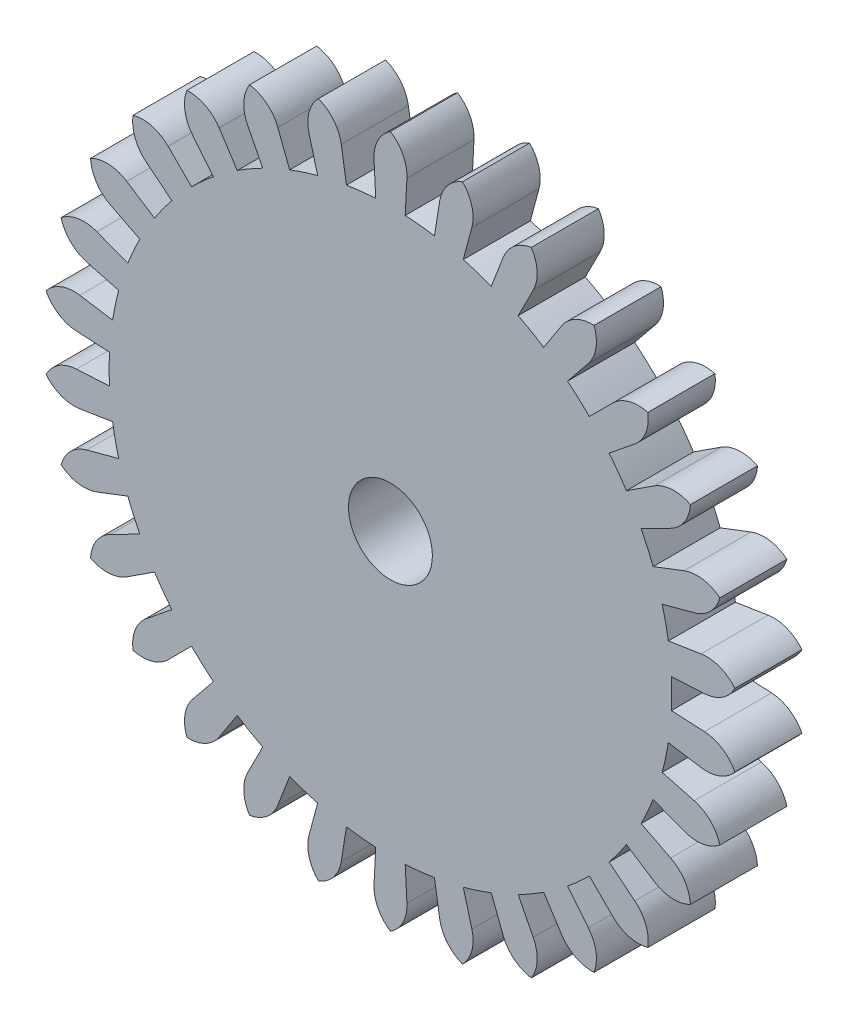
SolidWorks part; units mm, degrees
material "AISI 347 Annealed Stainless Steel (SS)"
ref_plane "Front Plane" through (0, 0, 0) normal (0, 0, 1) x (1, 0, 0)
ref_plane "Top Plane" through (0, 0, 0) normal (0, 1, 0) x (1, 0, 0)
ref_plane "Right Plane" through (0, 0, 0) normal (1, 0, 0) x (0, 0, -1)
sketch "Sketch1" plane through (0, 0, 0) normal (0, 0, 1) x (1, 0, 0)
  line L0 (0, 0) -> (0, 5.0077) construction
  line L1 (-0.1756, 3.3504) -> (-0.1963, 3.7449)
  line L2 (0.1756, 3.3504) -> (0.1963, 3.7449)
  line L3 (0.5248, 3.3137) -> (0.5866, 3.7038)
  line L4 (0.8684, 3.2407) -> (0.9706, 3.6222)
  line L5 (1.2023, 3.1322) -> (1.3439, 3.5009)
  line L6 (1.5232, 2.9893) -> (1.7025, 3.3413)
  line L7 (1.8272, 2.8138) -> (2.0424, 3.145)
  line L8 (2.1114, 2.6073) -> (2.36, 2.9143)
  line L9 (2.3723, 2.3724) -> (2.6516, 2.6517)
  line L10 (2.6073, 2.1114) -> (2.9143, 2.3599)
  line L11 (2.8137, 1.8273) -> (3.145, 2.0424)
  line L12 (2.9893, 1.5231) -> (3.3413, 1.7024)
  line L13 (3.1322, 1.2023) -> (3.5009, 1.3439)
  line L14 (3.2407, 0.8683) -> (3.6222, 0.9705)
  line L15 (3.3137, 0.5249) -> (3.7038, 0.5867)
  line L16 (3.3504, 0.1756) -> (3.7449, 0.1962)
  line L17 (3.3504, -0.1756) -> (3.7449, -0.1962)
  line L18 (3.3137, -0.5249) -> (3.7038, -0.5867)
  line L19 (3.2407, -0.8683) -> (3.6222, -0.9705)
  line L20 (3.1322, -1.2023) -> (3.5009, -1.3439)
  line L21 (2.9893, -1.5231) -> (3.3413, -1.7024)
  line L22 (2.8137, -1.8273) -> (3.145, -2.0424)
  line L23 (2.6073, -2.1114) -> (2.9143, -2.3599)
  line L24 (2.3723, -2.3724) -> (2.6516, -2.6517)
  line L25 (2.1114, -2.6073) -> (2.36, -2.9143)
  line L26 (1.8272, -2.8138) -> (2.0424, -3.145)
  line L27 (1.5232, -2.9893) -> (1.7025, -3.3413)
  line L28 (1.2023, -3.1322) -> (1.3439, -3.5009)
  line L29 (0.8684, -3.2407) -> (0.9706, -3.6222)
  line L30 (0.5248, -3.3137) -> (0.5866, -3.7038)
  line L31 (0.1756, -3.3504) -> (0.1963, -3.7449)
  line L32 (-0.1756, -3.3504) -> (-0.1963, -3.7449)
  line L33 (-0.5248, -3.3137) -> (-0.5866, -3.7038)
  line L34 (-0.8684, -3.2407) -> (-0.9706, -3.6222)
  line L35 (-1.2023, -3.1322) -> (-1.3439, -3.5009)
  line L36 (-1.5232, -2.9893) -> (-1.7025, -3.3413)
  line L37 (-1.8272, -2.8138) -> (-2.0424, -3.145)
  line L38 (-2.1114, -2.6073) -> (-2.36, -2.9143)
  line L39 (-2.3723, -2.3724) -> (-2.6516, -2.6517)
  line L40 (-2.6073, -2.1114) -> (-2.9143, -2.3599)
  line L41 (-2.8137, -1.8273) -> (-3.145, -2.0424)
  line L42 (-2.9893, -1.5231) -> (-3.3413, -1.7024)
  line L43 (-3.1322, -1.2023) -> (-3.5009, -1.3439)
  line L44 (-3.2407, -0.8683) -> (-3.6222, -0.9705)
  line L45 (-3.3137, -0.5249) -> (-3.7038, -0.5867)
  line L46 (-3.3504, -0.1756) -> (-3.7449, -0.1962)
  line L47 (-3.3504, 0.1756) -> (-3.7449, 0.1962)
  line L48 (-3.3137, 0.5249) -> (-3.7038, 0.5867)
  line L49 (-3.2407, 0.8683) -> (-3.6222, 0.9705)
  line L50 (-3.1322, 1.2023) -> (-3.5009, 1.3439)
  line L51 (-2.9893, 1.5231) -> (-3.3413, 1.7024)
  line L52 (-2.8137, 1.8273) -> (-3.145, 2.0424)
  line L53 (-2.6073, 2.1114) -> (-2.9143, 2.3599)
  line L54 (-2.3723, 2.3724) -> (-2.6516, 2.6517)
  line L55 (-2.1114, 2.6073) -> (-2.36, 2.9143)
  line L56 (-1.8272, 2.8138) -> (-2.0424, 3.145)
  line L57 (-1.5232, 2.9893) -> (-1.7025, 3.3413)
  line L58 (-1.2023, 3.1322) -> (-1.3439, 3.5009)
  line L59 (-0.8684, 3.2407) -> (-0.9706, 3.6222)
  line L60 (-0.5248, 3.3137) -> (-0.5866, 3.7038)
  arc A0 (0.5248, 3.3137) -> (0.1756, 3.3504) centre (0, 0) ccw
  arc A1 (1.2023, 3.1322) -> (0.8684, 3.2407) centre (0, 0) ccw
  arc A2 (-0.1756, 3.3504) -> (-0.5248, 3.3137) centre (0, 0) ccw
  arc A3 (0.1963, 3.7449) -> (0, 4.13) centre (-0.2353, 3.7675) ccw
  arc A4 (-0.1963, 3.7449) -> (0, 4.13) centre (0.2353, 3.7675) cw
  arc A5 (0.9706, 3.6222) -> (0.8587, 4.0397) centre (0.5531, 3.7341) ccw
  arc A6 (0.5866, 3.7038) -> (0.8587, 4.0397) centre (1.0135, 3.6362) cw
  arc A7 (1.7025, 3.3413) -> (1.6798, 3.7729) centre (1.3174, 3.5375) ccw
  arc A8 (1.3439, 3.5009) -> (1.6798, 3.7729) centre (1.7474, 3.3461) cw
  arc A9 (2.36, 2.9143) -> (2.4276, 3.3412) centre (2.0241, 3.1863) ccw
  arc A10 (2.0424, 3.145) -> (2.4276, 3.3412) centre (2.4049, 2.9096) cw
  arc A11 (2.9143, 2.3599) -> (3.0692, 2.7635) centre (2.6423, 2.6958) ccw
  arc A12 (2.6516, 2.6517) -> (3.0692, 2.7635) centre (2.9572, 2.3461) cw
  arc A13 (3.3413, 1.7024) -> (3.5767, 2.065) centre (3.1451, 2.0875) ccw
  arc A14 (3.145, 2.0424) -> (3.5767, 2.065) centre (3.3804, 1.6799) cw
  arc A15 (3.6222, 0.9705) -> (3.9279, 1.2762) centre (3.5104, 1.388) ccw
  arc A16 (3.5009, 1.3439) -> (3.9279, 1.2762) centre (3.6558, 0.9404) cw
  arc A17 (3.7449, 0.1962) -> (4.1074, 0.4317) centre (3.7222, 0.6278) ccw
  arc A18 (3.7038, 0.5867) -> (4.1074, 0.4317) centre (3.7714, 0.1598) cw
  arc A19 (3.7038, -0.5867) -> (4.1074, -0.4317) centre (3.7714, -0.1598) ccw
  arc A20 (3.7449, -0.1962) -> (4.1074, -0.4317) centre (3.7222, -0.6278) cw
  arc A21 (3.5009, -1.3439) -> (3.9279, -1.2762) centre (3.6558, -0.9404) ccw
  arc A22 (3.6222, -0.9705) -> (3.9279, -1.2762) centre (3.5104, -1.388) cw
  arc A23 (3.145, -2.0424) -> (3.5767, -2.065) centre (3.3804, -1.6799) ccw
  arc A24 (3.3413, -1.7024) -> (3.5767, -2.065) centre (3.1451, -2.0875) cw
  arc A25 (2.6516, -2.6517) -> (3.0692, -2.7635) centre (2.9572, -2.3461) ccw
  arc A26 (2.9143, -2.3599) -> (3.0692, -2.7635) centre (2.6423, -2.6958) cw
  arc A27 (2.0424, -3.145) -> (2.4276, -3.3412) centre (2.4049, -2.9096) ccw
  arc A28 (2.36, -2.9143) -> (2.4276, -3.3412) centre (2.0241, -3.1863) cw
  arc A29 (1.3439, -3.5009) -> (1.6798, -3.7729) centre (1.7474, -3.3461) ccw
  arc A30 (1.7025, -3.3413) -> (1.6798, -3.7729) centre (1.3174, -3.5375) cw
  arc A31 (0.5866, -3.7038) -> (0.8587, -4.0397) centre (1.0135, -3.6362) ccw
  arc A32 (0.9706, -3.6222) -> (0.8587, -4.0397) centre (0.5531, -3.7341) cw
  arc A33 (-0.1963, -3.7449) -> (0, -4.13) centre (0.2353, -3.7675) ccw
  arc A34 (0.1963, -3.7449) -> (0, -4.13) centre (-0.2353, -3.7675) cw
  arc A35 (-0.9706, -3.6222) -> (-0.8587, -4.0397) centre (-0.5531, -3.7341) ccw
  arc A36 (-0.5866, -3.7038) -> (-0.8587, -4.0397) centre (-1.0135, -3.6362) cw
  arc A37 (-1.7025, -3.3413) -> (-1.6798, -3.7729) centre (-1.3174, -3.5375) ccw
  arc A38 (-1.3439, -3.5009) -> (-1.6798, -3.7729) centre (-1.7474, -3.3461) cw
  arc A39 (-2.36, -2.9143) -> (-2.4276, -3.3412) centre (-2.0241, -3.1863) ccw
  arc A40 (-2.0424, -3.145) -> (-2.4276, -3.3412) centre (-2.4049, -2.9096) cw
  arc A41 (-2.9143, -2.3599) -> (-3.0692, -2.7635) centre (-2.6423, -2.6958) ccw
  arc A42 (-2.6516, -2.6517) -> (-3.0692, -2.7635) centre (-2.9572, -2.3461) cw
  arc A43 (-3.3413, -1.7024) -> (-3.5767, -2.065) centre (-3.1451, -2.0875) ccw
  arc A44 (-3.145, -2.0424) -> (-3.5767, -2.065) centre (-3.3804, -1.6799) cw
  arc A45 (-3.6222, -0.9705) -> (-3.9279, -1.2762) centre (-3.5104, -1.388) ccw
  arc A46 (-3.5009, -1.3439) -> (-3.9279, -1.2762) centre (-3.6558, -0.9404) cw
  arc A47 (-3.7449, -0.1962) -> (-4.1074, -0.4317) centre (-3.7222, -0.6278) ccw
  arc A48 (-3.7038, -0.5867) -> (-4.1074, -0.4317) centre (-3.7714, -0.1598) cw
  arc A49 (-3.7038, 0.5867) -> (-4.1074, 0.4317) centre (-3.7714, 0.1598) ccw
  arc A50 (-3.7449, 0.1962) -> (-4.1074, 0.4317) centre (-3.7222, 0.6278) cw
  arc A51 (-3.5009, 1.3439) -> (-3.9279, 1.2762) centre (-3.6558, 0.9404) ccw
  arc A52 (-3.6222, 0.9705) -> (-3.9279, 1.2762) centre (-3.5104, 1.388) cw
  arc A53 (-3.145, 2.0424) -> (-3.5767, 2.065) centre (-3.3804, 1.6799) ccw
  arc A54 (-3.3413, 1.7024) -> (-3.5767, 2.065) centre (-3.1451, 2.0875) cw
  arc A55 (-2.6516, 2.6517) -> (-3.0692, 2.7635) centre (-2.9572, 2.3461) ccw
  arc A56 (-2.9143, 2.3599) -> (-3.0692, 2.7635) centre (-2.6423, 2.6958) cw
  arc A57 (-2.0424, 3.145) -> (-2.4276, 3.3412) centre (-2.4049, 2.9096) ccw
  arc A58 (-2.36, 2.9143) -> (-2.4276, 3.3412) centre (-2.0241, 3.1863) cw
  arc A59 (-1.3439, 3.5009) -> (-1.6798, 3.7729) centre (-1.7474, 3.3461) ccw
  arc A60 (-1.7025, 3.3413) -> (-1.6798, 3.7729) centre (-1.3174, 3.5375) cw
  arc A61 (-0.5866, 3.7038) -> (-0.8587, 4.0397) centre (-1.0135, 3.6362) ccw
  arc A62 (-0.9706, 3.6222) -> (-0.8587, 4.0397) centre (-0.5531, 3.7341) cw
  arc A63 (-0.8684, 3.2407) -> (-1.2023, 3.1322) centre (0, 0) ccw
  arc A64 (-1.5232, 2.9893) -> (-1.8272, 2.8138) centre (0, 0) ccw
  arc A65 (-2.1114, 2.6073) -> (-2.3723, 2.3724) centre (0, 0) ccw
  arc A66 (-2.6073, 2.1114) -> (-2.8137, 1.8273) centre (0, 0) ccw
  arc A67 (-2.9893, 1.5231) -> (-3.1322, 1.2023) centre (0, 0) ccw
  arc A68 (-3.2407, 0.8683) -> (-3.3137, 0.5249) centre (0, 0) ccw
  arc A69 (-3.3504, 0.1756) -> (-3.3504, -0.1756) centre (0, 0) ccw
  arc A70 (-3.3137, -0.5249) -> (-3.2407, -0.8683) centre (0, 0) ccw
  arc A71 (-3.1322, -1.2023) -> (-2.9893, -1.5231) centre (0, 0) ccw
  arc A72 (-2.8137, -1.8273) -> (-2.6073, -2.1114) centre (0, 0) ccw
  arc A73 (-2.3723, -2.3724) -> (-2.1114, -2.6073) centre (0, 0) ccw
  arc A74 (-1.8272, -2.8138) -> (-1.5232, -2.9893) centre (0, 0) ccw
  arc A75 (-1.2023, -3.1322) -> (-0.8684, -3.2407) centre (0, 0) ccw
  arc A76 (-0.5248, -3.3137) -> (-0.1756, -3.3504) centre (0, 0) ccw
  arc A77 (0.1756, -3.3504) -> (0.5248, -3.3137) centre (0, 0) ccw
  arc A78 (0.8684, -3.2407) -> (1.2023, -3.1322) centre (0, 0) ccw
  arc A79 (1.5232, -2.9893) -> (1.8272, -2.8138) centre (0, 0) ccw
  arc A80 (2.1114, -2.6073) -> (2.3723, -2.3724) centre (0, 0) ccw
  arc A81 (2.6073, -2.1114) -> (2.8137, -1.8273) centre (0, 0) ccw
  arc A82 (2.9893, -1.5231) -> (3.1322, -1.2023) centre (0, 0) ccw
  arc A83 (3.2407, -0.8683) -> (3.3137, -0.5249) centre (0, 0) ccw
  arc A84 (3.3504, -0.1756) -> (3.3504, 0.1756) centre (0, 0) ccw
  arc A85 (3.3137, 0.5249) -> (3.2407, 0.8683) centre (0, 0) ccw
  arc A86 (3.1322, 1.2023) -> (2.9893, 1.5231) centre (0, 0) ccw
  arc A87 (2.8137, 1.8273) -> (2.6073, 2.1114) centre (0, 0) ccw
  arc A88 (2.3723, 2.3724) -> (2.1114, 2.6073) centre (0, 0) ccw
  arc A89 (1.8272, 2.8138) -> (1.5232, 2.9893) centre (0, 0) ccw
  circle A90 centre (0, 0) radius 0.5
  point P218 (0, 0)
  dimension "D1" = 1
  dimension "D2" = 6.71
  dimension "D3" = 8.26
  dimension "D4" = 30
extrude "Boss-Extrude1" add sketch "Sketch1" along normal blind 0.8
